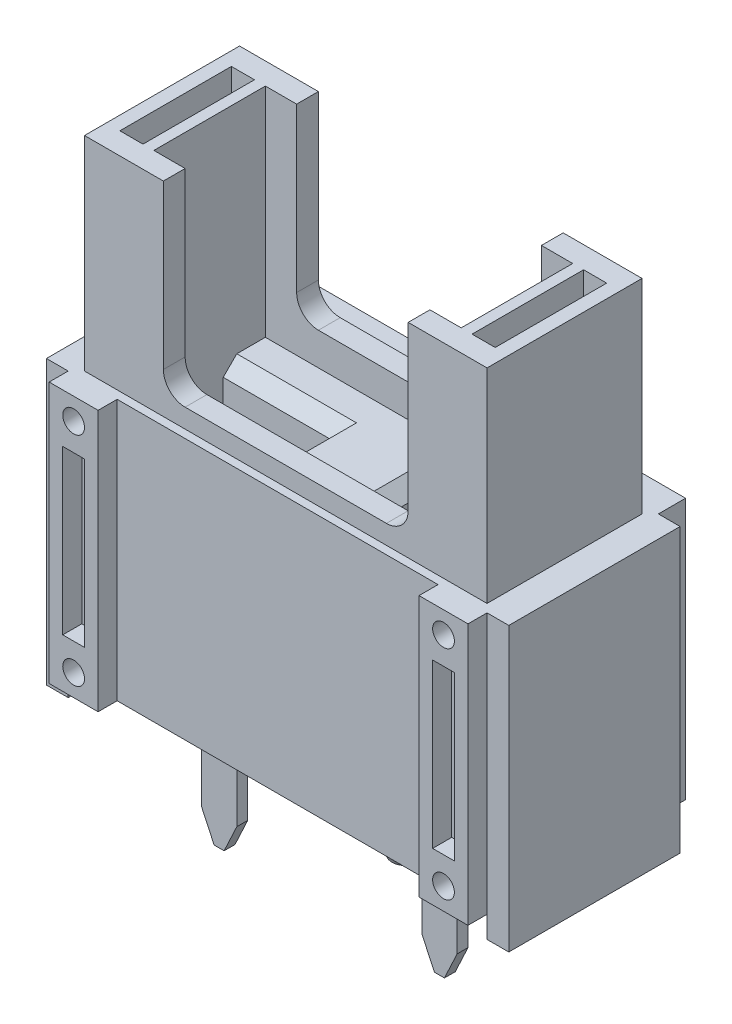
SolidWorks part; units mm, degrees
ref_plane "Front Plane" through (0, 0, 0) normal (0, 0, 1) x (1, 0, 0)
ref_plane "Top Plane" through (0, 0, 0) normal (0, 1, 0) x (1, 0, 0)
ref_plane "Right Plane" through (0, 0, 0) normal (1, 0, 0) x (0, 0, -1)
sketch "Sketch1" plane through (0, 0, 0) normal (0, 1, 0) x (1, 0, 0)
  line L0 (0, 0) -> (0, 6.3)
  line L1 (0, 6.3) -> (0.8, 6.3)
  line L2 (0.8, 6.3) -> (0.8, 7.3)
  line L3 (0.8, 7.3) -> (16.2, 7.3)
  line L4 (16.2, 7.3) -> (16.2, 6.3)
  line L5 (16.2, 6.3) -> (17, 6.3)
  line L6 (17, 6.3) -> (17, 0)
  line L7 (17, 0) -> (16.2, 0)
  line L8 (16.2, 0) -> (16.2, -0.7)
  line L9 (16.2, -0.7) -> (14.4, -0.7)
  line L10 (14.4, -0.7) -> (14.4, 0)
  line L11 (14.4, 0) -> (2.6, 0)
  line L12 (2.6, 0) -> (2.6, -0.7)
  line L13 (2.6, -0.7) -> (0.8, -0.7)
  line L14 (0.8, -0.7) -> (0.8, 0)
  line L15 (0.8, 0) -> (0, 0)
  dimension "D1" = 17
  dimension "D2" = 15.4
  dimension "D3" = 0.8
  dimension "D4" = 6.3
  dimension "D5" = 1
  dimension "D6" = 1.8
  dimension "D7" = 1.8
  dimension "D8" = 0.7
extrude "Boss-Extrude1" add sketch "Sketch1" along normal blind 10.4
sketch "Sketch2" plane through (0, 0, 0) normal (0, -1, 0) x (1, 0, 0)
  line L1 (0.8, 1.5734) -> (16.2, 1.5734)
  line L2 (0.8, 1.5734) -> (0.8, -8.9232)
  line L3 (0.8, -8.9232) -> (16.2, -8.9232)
  line L4 (16.2, 1.5734) -> (16.2, -8.9232)
  line L5 (17, 0) -> (17, -6.3) construction
  line L6 (0, -6.3) -> (0, 0) construction
  dimension "D1" = 0.8
  dimension "D2" = 0.8
extrude "Cut-Extrude1" cut sketch "Sketch2" against normal blind 0.8
sketch "Sketch3" plane through (0, 10.4, 0) normal (0, 1, 0) x (1, 0, 0)
  line L0 (16.2, 7.3) -> (0.8, 7.3) construction
  line L1 (1.1, 6) -> (15.9, 6)
  line L2 (1.1, 6) -> (1.1, 0.3)
  line L3 (1.1, 0.3) -> (15.9, 0.3)
  line L4 (15.9, 6) -> (15.9, 0.3)
  line L5 (0, 6.3) -> (0, 0) construction
  dimension "D1" = 14.8
  dimension "D2" = 5.7
  dimension "D3" = 1.3
  dimension "D4" = 1.1
extrude "Boss-Extrude2" add sketch "Sketch3" along normal blind 7.5
sketch "Sketch4" plane through (0, 0, -0.3) normal (0, 0, 1) x (1, 0, 0)
  line L0 (4, 17.9) -> (4, 11.9)
  line L1 (1.1, 17.9) -> (15.9, 17.9) construction
  line L2 (4.8, 11.1) -> (12.2, 11.1)
  line L3 (13, 11.9) -> (13, 17.9)
  line L4 (13, 17.9) -> (4, 17.9)
  line L5 (1.1, 10.4) -> (15.9, 10.4) construction
  line L6 (15.9, 17.9) -> (15.9, 10.4) construction
  line L7 (1.1, 17.9) -> (1.1, 10.4) construction
  arc A0 (13, 11.9) -> (12.2, 11.1) centre (12.2, 11.9) cw
  arc A1 (4, 11.9) -> (4.8, 11.1) centre (4.8, 11.9) ccw
  dimension "D4" = 0.8
  dimension "D1" = 0.7
  dimension "D2" = 2.9
  dimension "D3" = 2.9
extrude "Cut-Extrude2" cut sketch "Sketch4" against normal through all
sketch "Sketch5" plane through (0, 17.9, 0) normal (0, 1, 0) x (1, 0, 0)
  line L0 (15.9, 6) -> (13, 6) construction
  line L1 (2.85, 5.2) -> (14.15, 5.2)
  line L2 (2.85, 5.2) -> (2.85, 1.1)
  line L3 (2.85, 1.1) -> (14.15, 1.1)
  line L4 (14.15, 5.2) -> (14.15, 1.1)
  line L5 (13, 0.3) -> (15.9, 0.3) construction
  line L6 (1.1, 6) -> (1.1, 0.3) construction
  line L7 (15.9, 0.3) -> (15.9, 6) construction
  dimension "D1" = 0.8
  dimension "D2" = 0.8
  dimension "D3" = 1.75
  dimension "D4" = 1.75
extrude "Cut-Extrude3" cut sketch "Sketch5" against normal blind 8
sketch "Sketch6" plane through (0, 17.9, 0) normal (0, 1, 0) x (1, 0, 0)
  line L0 (15.9, 0.3) -> (15.9, 6) construction
  line L1 (14.55, 5.2) -> (15.4, 5.2)
  line L2 (14.55, 5.2) -> (14.55, 1.1)
  line L3 (14.55, 1.1) -> (15.4, 1.1)
  line L4 (15.4, 5.2) -> (15.4, 1.1)
  line L6 (14.15, 5.2) -> (13, 5.2) construction
  line L7 (2.85, 1.1) -> (14.15, 1.1) construction
  line L8 (14.15, 1.1) -> (14.15, 5.2) construction
  line L9 (8.5, 8.7149) -> (8.5, -1.5162) construction
  line L10 (2.45, 1.1) -> (1.6, 1.1)
  line L11 (1.6, 5.2) -> (1.6, 1.1)
  line L12 (2.45, 5.2) -> (2.45, 1.1)
  line L13 (2.45, 5.2) -> (1.6, 5.2)
  dimension "D1" = 0.5
  dimension "D2" = 0.4
extrude "Cut-Extrude4" cut sketch "Sketch6" against normal blind 8
sketch "Sketch7" plane through (0, 0, 0.7) normal (0, 0, 1) x (1, 0, 0)
  line L0 (16.2, 10.4) -> (16.2, 0.8) construction
  line L1 (14.9, 8.6) -> (15.7, 8.6)
  line L2 (14.9, 8.6) -> (14.9, 2.6)
  line L3 (14.9, 2.6) -> (15.7, 2.6)
  line L4 (15.7, 8.6) -> (15.7, 2.6)
  line L5 (14.4, 10.4) -> (14.4, 0.8) construction
  line L6 (16.2, 0.8) -> (14.4, 0.8) construction
  line L7 (14.4, 10.4) -> (16.2, 10.4) construction
  line L8 (8.5, 11.9826) -> (8.5, -0.6777) construction
  line L9 (2.1, 2.6) -> (1.3, 2.6)
  line L10 (1.3, 8.6) -> (1.3, 2.6)
  line L11 (2.1, 8.6) -> (2.1, 2.6)
  line L12 (2.1, 8.6) -> (1.3, 8.6)
  circle A0 centre (15.3, 9.6) radius 0.4
  circle A1 centre (15.3, 1.6) radius 0.4
  circle A2 centre (1.7, 1.6) radius 0.4
  circle A3 centre (1.7, 9.6) radius 0.4
  point P10 (15.3, 10.4)
  dimension "D5" = 0.8
  dimension "D7" = 0.8
  dimension "D1" = 0.5
  dimension "D2" = 0.5
  dimension "D3" = 1.8
  dimension "D4" = 1.8
  dimension "D6" = 0.8
  dimension "D8" = 0.8
extrude "Cut-Extrude5" cut sketch "Sketch7" against normal blind 0.7
sketch "Sketch8" plane through (0, 0.8, 0) normal (0, -1, 0) x (1, 0, 0)
  line L0 (8.5, 0) -> (8.5, -7.3) construction
  line L1 (14.4, 0) -> (2.6, 0) construction
  line L2 (0.8, -7.3) -> (16.2, -7.3) construction
  circle A0 centre (8.5, -4.7) radius 1.19
  dimension "D1" = 2.38
  dimension "D2" = 2.6
extrude "Boss-Extrude3" add sketch "Sketch8" along normal blind 4.3
sketch "Sketch9" plane through (0, 0.8, 0) normal (0, -1, 0) x (1, 0, 0)
  circle A0 centre (8.5, -4.7) radius 2.1494
  circle A1 centre (8.5, -4.7) radius 1.05
  dimension "D1" = 2.1
extrude "Cut-Extrude6" cut sketch "Sketch9" along normal blind 2.3
chamfer "Chamfer1" distance 1.5 angle 25 1 edges at (8.5, -3.5, -5.89)
sketch "Sketch10" plane through (0, -3.5, 0) normal (0, -1, 0) x (1, 0, 0)
  line L1 (6.623, -4.5) -> (10.377, -4.5)
  line L2 (6.623, -4.5) -> (6.623, -4.9)
  line L3 (6.623, -4.9) -> (10.377, -4.9)
  line L4 (10.377, -4.5) -> (10.377, -4.9)
  line L5 (6.623, -4.5) -> (10.377, -4.9) construction
  line L6 (6.623, -4.9) -> (10.377, -4.5) construction
  point P0 (8.5, -4.7)
  dimension "D1" = 0.4
extrude "Cut-Extrude7" cut sketch "Sketch10" against normal blind 4
sketch "Sketch11" plane through (0, 0.8, 0) normal (0, -1, 0) x (1, 0, 0)
  line L0 (8.9479, -4.5) -> (8.0521, -4.5) construction
  line L1 (11.9, -1.9) -> (13.2, -1.9)
  line L2 (11.9, -1.9) -> (11.9, -2.3)
  line L3 (11.9, -2.3) -> (13.2, -2.3)
  line L4 (13.2, -1.9) -> (13.2, -2.3)
  line L5 (11.9, -1.9) -> (13.2, -2.3) construction
  line L6 (11.9, -2.3) -> (13.2, -1.9) construction
  line L7 (8.5, -8.5483) -> (8.5, 2.7606) construction
  line L8 (5.1, -2.3) -> (3.8, -1.9) construction
  line L9 (5.1, -1.9) -> (3.8, -2.3) construction
  line L10 (3.8, -1.9) -> (3.8, -2.3)
  line L11 (5.1, -2.3) -> (3.8, -2.3)
  line L12 (5.1, -1.9) -> (5.1, -2.3)
  line L13 (5.1, -1.9) -> (3.8, -1.9)
  arc A0 (9.5308, -4.9) -> (9.5308, -4.5) centre (8.5, -4.7) ccw construction
  point P0 (12.55, -2.1)
  point P5 (9.55, -4.7)
  point P9 (8.5, -4.5)
  point P18 (4.45, -2.1)
  dimension "D1" = 1.3
  dimension "D2" = 2.6
  dimension "D3" = 0.4
  dimension "D4" = 4.05
extrude "Boss-Extrude4" add sketch "Sketch11" along normal blind 4.71
chamfer "Chamfer2" distance 1 angle 25 4 edges at (3.8, -3.91, -2.1) (5.1, -3.91, -2.1) (11.9, -3.91, -2.1) (13.2, -3.91, -2.1)
fillet "Fillet1" radius 0.3 4 edges at (13.2, 0.8, -2.1) (11.9, 0.8, -2.1) (5.1, 0.8, -2.1) (3.8, 0.8, -2.1)
sketch "Sketch12" plane through (0, 0, -7.3) normal (0, 0, -1) x (-1, 0, 0)
  line L0 (-8.5, 10.4) -> (-8.5, 0.8) construction
  line L1 (-12, 8.35) -> (-5, 8.35)
  line L2 (-12.5, 7.85) -> (-12.5, 3.35)
  line L3 (-12, 2.85) -> (-5, 2.85)
  line L4 (-4.5, 7.85) -> (-4.5, 3.35)
  line L5 (-12.5, 8.35) -> (-4.5, 2.85) construction
  line L6 (-12.5, 2.85) -> (-4.5, 8.35) construction
  line L7 (-16.2, 10.4) -> (-0.8, 10.4) construction
  line L8 (-0.8, 0.8) -> (-16.2, 0.8) construction
  arc A0 (-12.5, 3.35) -> (-12, 2.85) centre (-12, 3.35) ccw
  arc A1 (-4.5, 3.35) -> (-5, 2.85) centre (-5, 3.35) cw
  arc A2 (-5, 8.35) -> (-4.5, 7.85) centre (-5, 7.85) cw
  arc A3 (-12, 8.35) -> (-12.5, 7.85) centre (-12, 7.85) ccw
  point P0 (-8.5, 5.6)
  dimension "D3" = 0.5
  dimension "D1" = 5.5
  dimension "D2" = 8
extrude "Cut-Extrude8" cut sketch "Sketch12" against normal blind 0.05
sketch "Sketch13" plane through (0, 0, -7.25) normal (0, 0, -1) x (-1, 0, 0)
  text T0 "32V    20A\r\n          MAX" font "Century Gothic" height in points 3
extrude "Boss-Extrude5" add sketch "Sketch13" along normal blind 0.05
sketch "Sketch14" plane through (0, 0, -7.3) normal (0, 0, -1) x (-1, 0, 0)
  text T0 "153" font "Century Gothic" height in points 3
extrude "Cut-Extrude10" cut sketch "Sketch14" against normal blind 0.03
sketch "Sketch15" plane through (0, 0.8, 0) normal (0, -1, 0) x (1, 0, 0)
  circle A0 centre (4.45, -2.1) radius 1.45
  circle A1 centre (12.55, -2.1) radius 1.45
  circle A2 centre (4.45, -2.1) radius 1.15
  circle A3 centre (12.55, -2.1) radius 1.15
  dimension "D1" = 2.9
  dimension "D2" = 2.9
  dimension "D3" = 2.3
  dimension "D4" = 2.3
extrude "Cut-Extrude11" cut sketch "Sketch15" against normal blind 0.1
sketch "Sketch16" plane through (0, 9.9, 0) normal (0, 1, 0) x (1, 0, 0)
  line L0 (2.85, 5.2) -> (2.85, 1.1) construction
  line L1 (2.85, 3.65) -> (6.75, 3.65)
  line L2 (2.85, 3.65) -> (2.85, 2.65)
  line L3 (2.85, 2.65) -> (6.75, 2.65)
  line L4 (6.75, 3.65) -> (6.75, 2.65)
  line L5 (2.85, 3.65) -> (6.75, 2.65) construction
  line L6 (2.85, 2.65) -> (6.75, 3.65) construction
  line L7 (2.85, 3.15) -> (14.15, 3.15) construction
  line L8 (14.15, 1.1) -> (14.15, 5.2) construction
  line L9 (8.5, 5.2) -> (8.5, 1.1) construction
  line L10 (14.15, 5.2) -> (2.85, 5.2) construction
  line L11 (2.85, 1.1) -> (14.15, 1.1) construction
  line L12 (14.15, 2.65) -> (10.25, 3.65) construction
  line L13 (14.15, 3.65) -> (10.25, 2.65) construction
  line L14 (10.25, 3.65) -> (10.25, 2.65)
  line L15 (14.15, 2.65) -> (10.25, 2.65)
  line L16 (14.15, 3.65) -> (14.15, 2.65)
  line L17 (14.15, 3.65) -> (10.25, 3.65)
  point P0 (4.8, 3.15)
  point P21 (12.2, 3.15)
  dimension "D1" = 1
  dimension "D2" = 3.9
extrude "Cut-Extrude12" cut sketch "Sketch16" against normal blind 8
chamfer "Chamfer3" distance 0.5 angle 45 6 edges at (12.2, 9.9, -2.65) (10.25, 9.9, -3.15) (12.2, 9.9, -3.65) (6.75, 9.9, -3.15)
